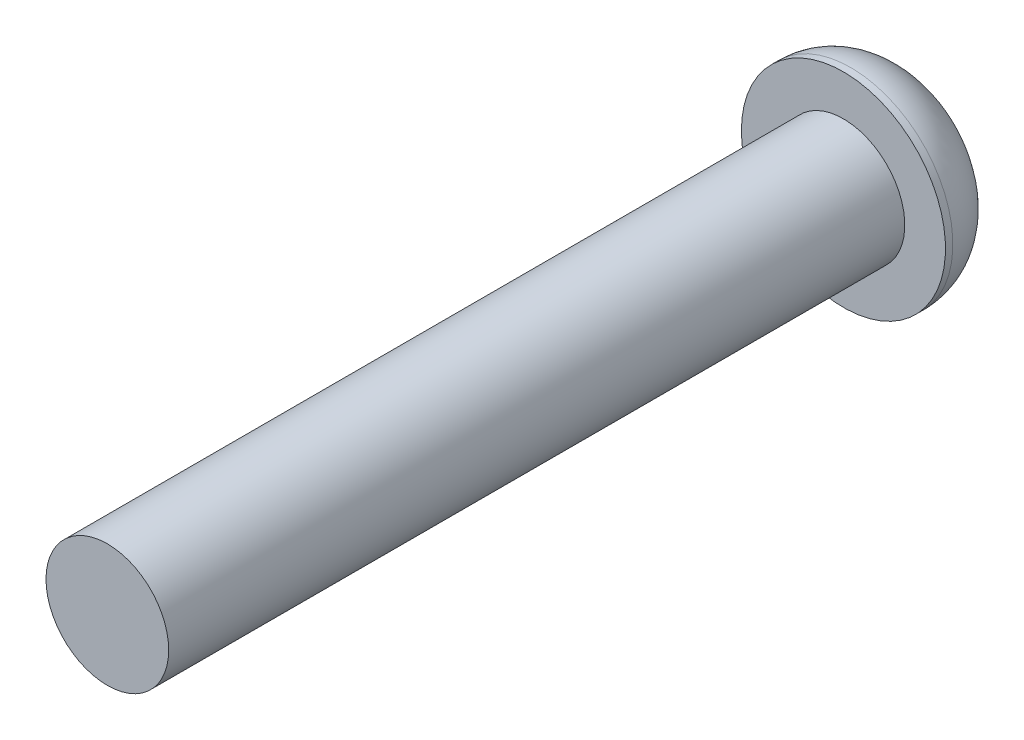
SolidWorks part; units mm, degrees
ref_plane "Front Plane" through (0, 0, 0) normal (0, 0, 1) x (1, 0, 0)
ref_plane "Top Plane" through (0, 0, 0) normal (0, 1, 0) x (1, 0, 0)
ref_plane "Right Plane" through (0, 0, 0) normal (1, 0, 0) x (0, 0, -1)
sketch "Sketch1" plane through (0, 0, 0) normal (0, 0, 1) x (1, 0, 0)
  circle A0 centre (0, 0) radius 2.5
  dimension "D1" = 5
extrude "Boss-Extrude1" add sketch "Sketch1" along normal blind 30
sketch "Sketch2" plane through (0, 0, 0) normal (0, 0, -1) x (-1, 0, 0)
  circle A0 centre (0, 0) radius 4.1596
extrude "Boss-Extrude2" add sketch "Sketch2" along normal blind 2.8
fillet "Fillet1" radius 2.5 1 edges at (-4.1596, 0, -2.8)
sketch "Sketch3" plane through (0, 0, -2.8) normal (0, 0, -1) x (-1, 0, 0)
  line L1 (1.3924, -0.6365) -> (1.2475, 0.8876)
  line L2 (1.2475, 0.8876) -> (-0.145, 1.5241)
  line L3 (-0.145, 1.5241) -> (-1.3924, 0.6365)
  line L4 (-1.3924, 0.6365) -> (-1.2475, -0.8876)
  line L5 (-1.2475, -0.8876) -> (0.145, -1.5241)
  line L6 (0.145, -1.5241) -> (1.3924, -0.6365)
  circle A0 centre (0, 0) radius 1.3259 construction
extrude "Cut-Extrude1" cut sketch "Sketch3" against normal blind 2
